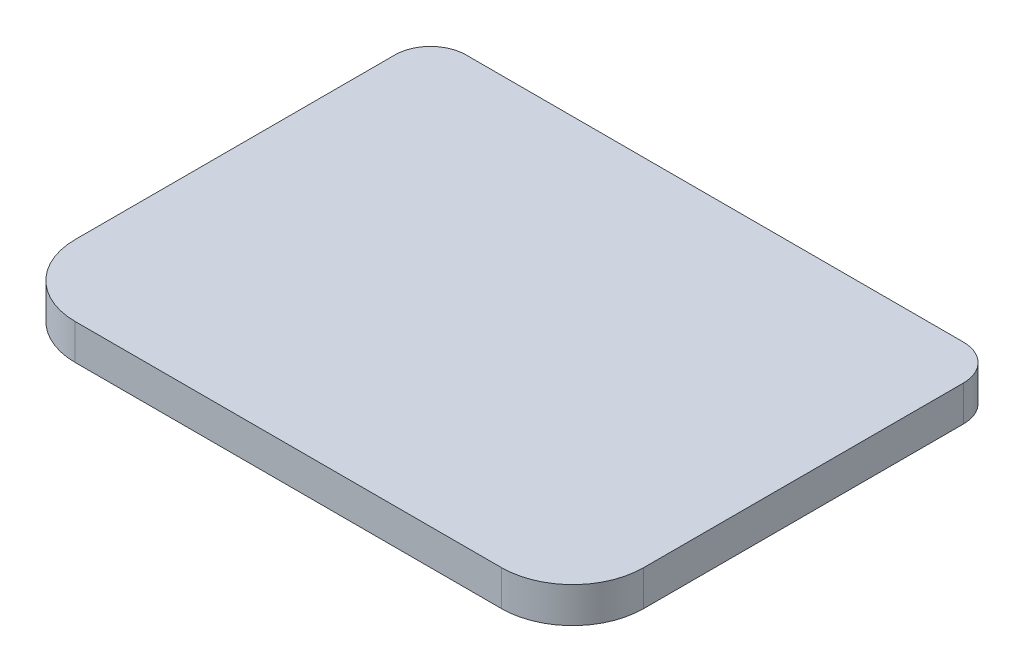
SolidWorks part; units mm, degrees
ref_plane "Front Plane" through (0, 0, 0) normal (0, 0, 1) x (1, 0, 0)
ref_plane "Top Plane" through (0, 0, 0) normal (0, 1, 0) x (1, 0, 0)
ref_plane "Right Plane" through (0, 0, 0) normal (1, 0, 0) x (0, 0, -1)
sketch "Sketch1" plane through (0, 0, 0) normal (0, 1, 0) x (1, 0, 0)
  line L1 (-25.4, 19.05) -> (25.4, 19.05)
  line L2 (-25.4, 19.05) -> (-25.4, -19.05)
  line L3 (-25.4, -19.05) -> (25.4, -19.05)
  line L4 (25.4, 19.05) -> (25.4, -19.05)
  line L5 (-25.4, 19.05) -> (25.4, -19.05) construction
  line L6 (-25.4, -19.05) -> (25.4, 19.05) construction
  point P0 (0, 0)
  dimension "D1" = 50.8
  dimension "D2" = 38.1
extrude "Boss-Extrude1" add sketch "Sketch1" along normal blind 3.175
fillet "Fillet1" radius 6.35 2 edges at (25.4, 1.5875, 19.05) (-25.4, 1.5875, 19.05)
fillet "Fillet2" radius 3.175 2 edges at (25.4, 1.5875, -19.05) (-25.4, 1.5875, -19.05)
